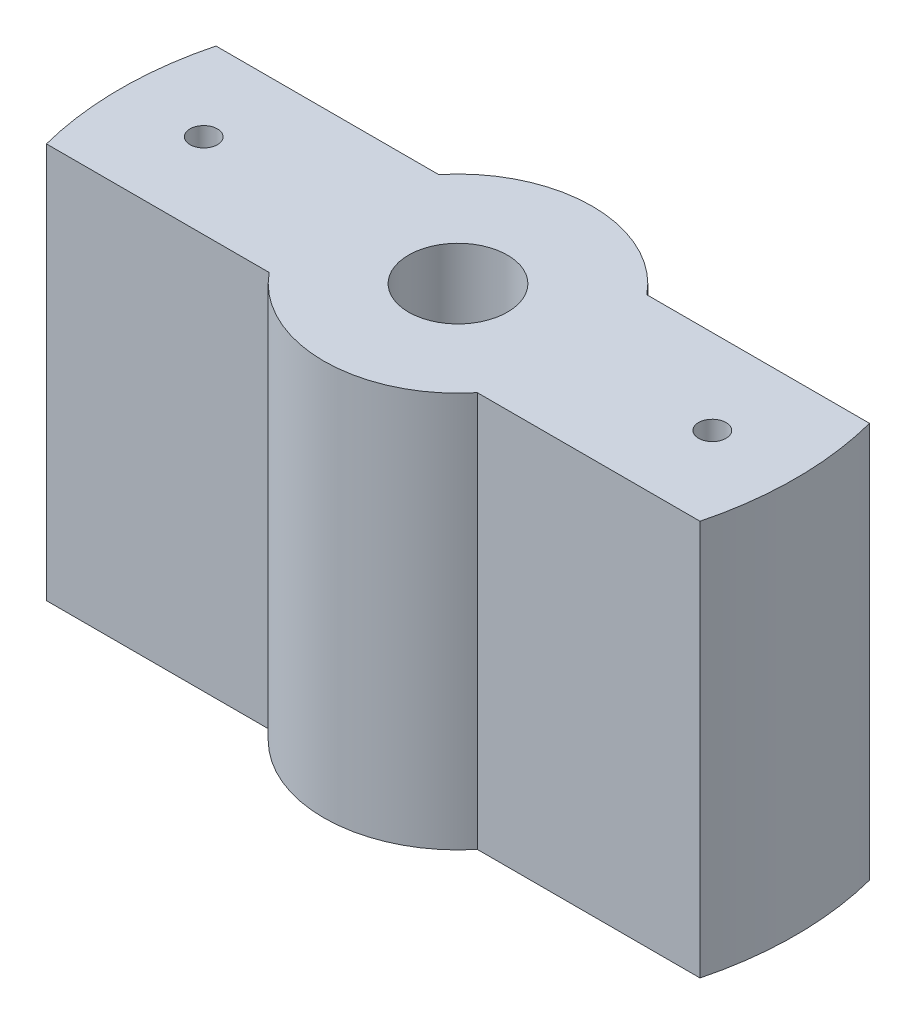
SolidWorks part; units mm, degrees
ref_plane "Спереди" through (0, 0, 0) normal (0, 0, 1) x (1, 0, 0)
ref_plane "Сверху" through (0, 0, 0) normal (0, 1, 0) x (1, 0, 0)
ref_plane "Справа" through (0, 0, 0) normal (1, 0, 0) x (0, 0, -1)
sketch "Эскиз1" plane through (0, 0, 0) normal (0, 1, 0) x (1, 0, 0)
  line L0 (-95.271, 5.8634) -> (95.271, 5.8634) construction
  line L1 (73.4393, -13.1866) -> (23.3853, -13.1866)
  line L2 (0, 106.0034) -> (0, -90.9498) construction
  line L3 (73.4393, 24.9134) -> (23.3853, 24.9134)
  line L4 (-23.3853, 24.9134) -> (-73.4393, 24.9134)
  line L5 (-23.3853, -13.1866) -> (-73.4393, -13.1866)
  circle A0 centre (0, 5.8634) radius 11.1125
  arc A1 (-23.3853, -13.1866) -> (23.3853, -13.1866) centre (0, 5.8634) ccw
  arc A2 (-73.4393, 24.9134) -> (-73.4393, -13.1866) centre (0, 5.8634) ccw
  arc A3 (73.4393, -13.1866) -> (73.4393, 24.9134) centre (0, 5.8634) ccw
  circle A4 centre (-57.15, 5.8634) radius 3.084
  arc A5 (23.3853, 24.9134) -> (-23.3853, 24.9134) centre (0, 5.8634) ccw
  circle A6 centre (0, 5.8634) radius 30.1625 construction
  circle A7 centre (57.15, 5.8634) radius 3.084
  point P0 (-4.0901, -0.8035)
  point P12 (-75.8698, 5.8634)
  point P14 (0, -13.1866)
  point P21 (60, 0)
  point P43 (38.2522, 11.6949)
  dimension "D1" = 60.325
  dimension "D5" = 151.7396
  dimension "D2" = 22.225
  dimension "D7" = 57.15
  dimension "D3" = 38.1
  dimension "D4" = 146.8785
  dimension "D6" = 19.05
  dimension "D8" = 18.7198
extrude "Бобышка-Вытянуть1" add sketch "Эскиз1" along normal blind 88.9
